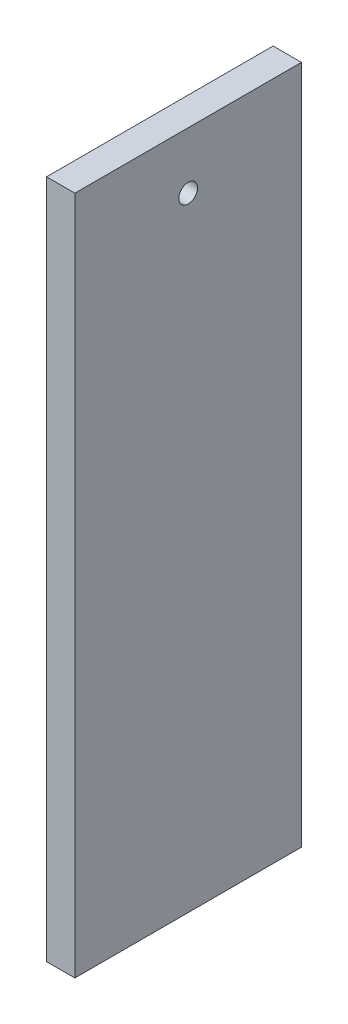
SolidWorks part; units mm, degrees
ref_plane "Front Plane" through (0, 0, 0) normal (0, 0, 1) x (1, 0, 0)
ref_plane "Top Plane" through (0, 0, 0) normal (0, 1, 0) x (1, 0, 0)
ref_plane "Right Plane" through (0, 0, 0) normal (1, 0, 0) x (0, 0, -1)
sketch "Sketch1" plane through (0, 0, 0) normal (1, 0, 0) x (0, 0, -1)
  line L1 (0, 0) -> (-40, 0)
  line L2 (0, 0) -> (0, 120)
  line L3 (0, 120) -> (-40, 120)
  line L4 (-40, 0) -> (-40, 120)
  dimension "D1" = 40
  dimension "D2" = 120
extrude "Boss-Extrude1" add sketch "Sketch1" along normal blind 5 contours L4 L3 L2 L1
sketch "Sketch2" plane through (5, 0, 0) normal (1, 0, 0) x (0, 0, -1)
  line L0 (-40, 120) -> (-20, 120)
  line L1 (0, 120) -> (-40, 120) construction
  line L2 (-20, 120) -> (-20, 0)
  line L3 (0, 0) -> (-40, 0) construction
  line L4 (-20, 60) -> (0, 60)
  line L5 (0, 0) -> (0, 120) construction
  line L6 (-20, 60) -> (-40, 60)
  line L7 (-40, 0) -> (-40, 120) construction
  line L8 (-40, 60) -> (-40, 120)
  line L9 (0, 60) -> (0, 120)
  circle A0 centre (-20, 110) radius 1.65
  dimension "D1" = 10
  dimension "D2" = 0
extrude "Cut-Extrude1" cut sketch "Sketch2" against normal blind 5 contours L2 A0 | L2 A0
